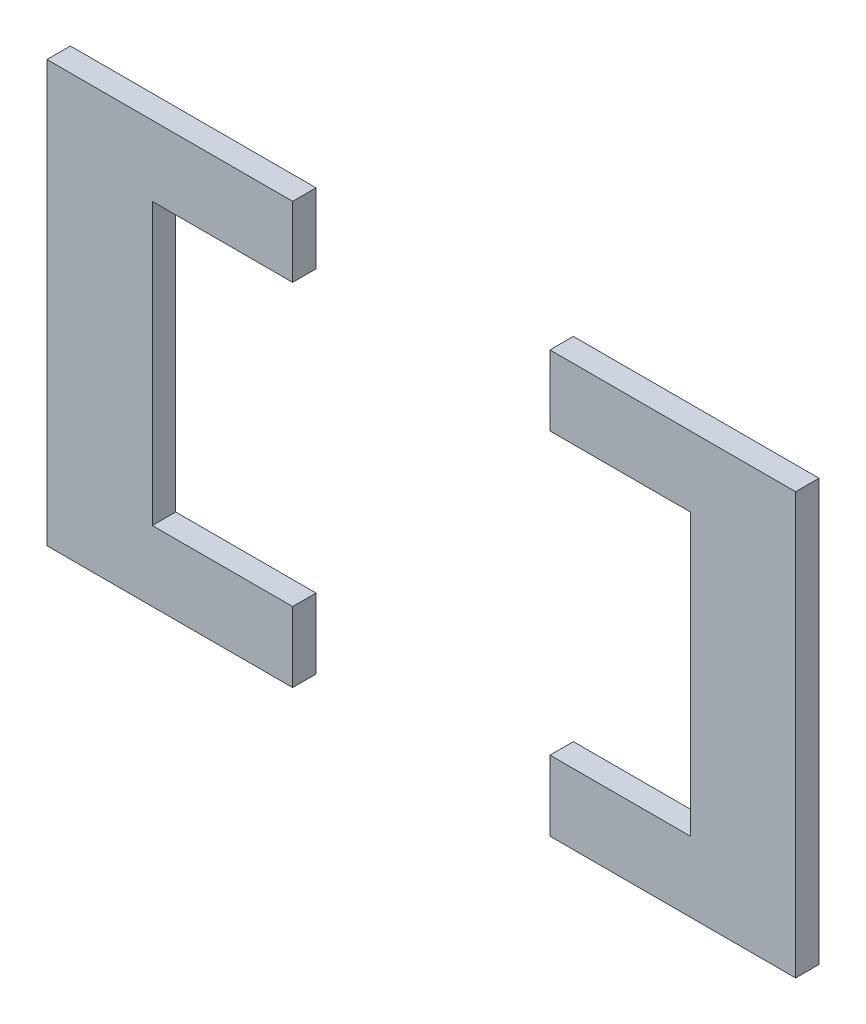
SolidWorks part; units mm, degrees
ref_plane "Front Plane" through (0, 0, 0) normal (0, 0, 1) x (1, 0, 0)
ref_plane "Top Plane" through (0, 0, 0) normal (0, 1, 0) x (1, 0, 0)
ref_plane "Right Plane" through (0, 0, 0) normal (1, 0, 0) x (0, 0, -1)
sketch "Sketch1" plane through (0, 0, 0) normal (0, 0, 1) x (1, 0, 0)
  line L0 (0, 66.5) -> (10.5, 66.5)
  line L1 (10.5, 66.5) -> (10.5, 48.5)
  line L2 (10.5, 48.5) -> (0, 48.5)
  line L3 (0, 48.5) -> (0, 51.5)
  line L5 (0, 51.5) -> (6, 51.5)
  line L6 (6, 51.5) -> (6, 63.5)
  line L7 (6, 63.5) -> (0, 63.5)
  line L9 (0, 63.5) -> (0, 66.5)
  line L10 (-5.5, 63.5) -> (-5.5, 51.5) construction
  line L11 (-11, 66.5) -> (-21.5, 66.5)
  line L12 (-21.5, 66.5) -> (-21.5, 48.5)
  line L13 (-21.5, 48.5) -> (-11, 48.5)
  line L14 (-11, 48.5) -> (-11, 51.5)
  line L15 (-11, 51.5) -> (-17, 51.5)
  line L16 (-17, 51.5) -> (-17, 63.5)
  line L17 (-17, 63.5) -> (-11, 63.5)
  line L18 (-11, 63.5) -> (-11, 66.5)
  dimension "D1" = 3
  dimension "D2" = 4.5
extrude "Boss-Extrude1" add sketch "Sketch1" along normal blind 1
